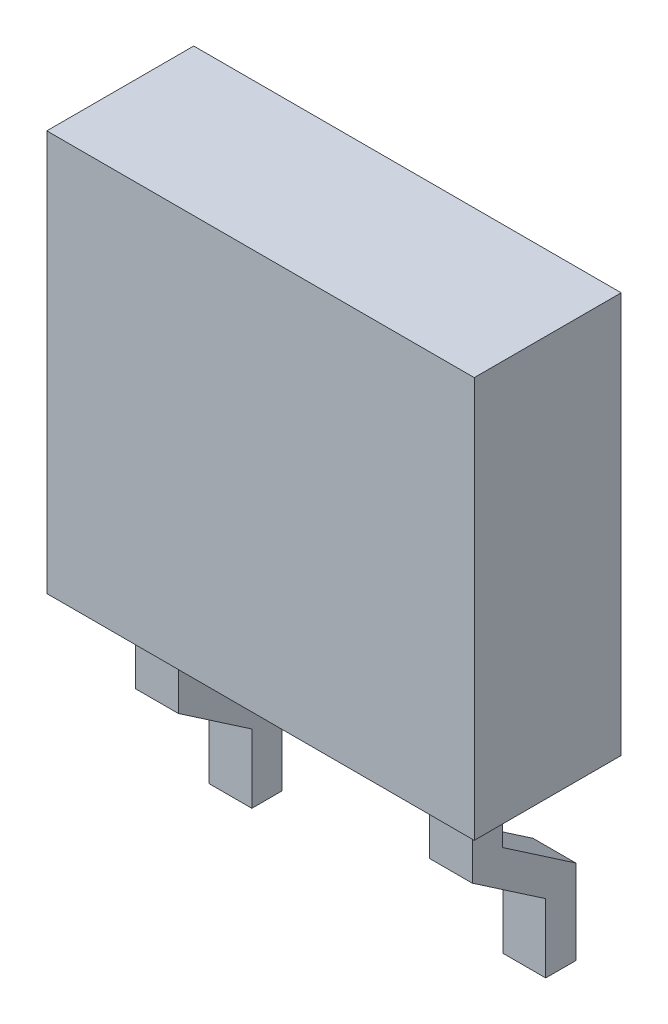
SolidWorks part; units mm, degrees
material "ABS"
ref_plane "Plan de face" through (0, 0, 0) normal (0, 0, 1) x (1, 0, 0)
ref_plane "Plan de dessus" through (0, 0, 0) normal (0, 1, 0) x (1, 0, 0)
ref_plane "Plan de droite" through (0, 0, 0) normal (1, 0, 0) x (0, 0, -1)
sketch "Esquisse1" plane through (0, 0, 0) normal (0, 0, 1) x (1, 0, 0)
  line L0 (3.2, 0) -> (3.2, -5.4078) construction
  line L1 (0, 0) -> (0.68, 0)
  line L2 (0, 0) -> (0, 6)
  line L3 (0, 6) -> (6.4, 6)
  line L4 (6.4, 0) -> (6.4, 6)
  line L5 (5.4, 1.3238) -> (5.4, -3.2603) construction
  line L6 (1.32, -3) -> (0.68, -3)
  line L7 (5.72, 0) -> (6.4, 0)
  line L8 (5.08, 0) -> (5.08, -3)
  line L9 (5.08, -3) -> (5.72, -3)
  line L10 (5.72, 0) -> (5.72, -3)
  line L11 (1.32, 0) -> (1.32, -3)
  line L12 (0.68, 0) -> (0.68, -3)
  line L13 (5.08, 0) -> (1.32, 0)
  dimension "D1" = 6.4
  dimension "D2" = 6
  dimension "D3" = 2.2
  dimension "D4" = 0.32
  dimension "D5" = 0.32
  dimension "D6" = 3
extrude "Extrusion1" add sketch "Esquisse1" along normal blind 2.2
sketch "Esquisse2" plane through (0.68, 0, 0) normal (-1, 0, 0) x (0, 0, 1)
  line L0 (0.45, -1.9712) -> (0.45, -3.3272)
  line L1 (1.55, 0) -> (4.1136, 0)
  line L2 (0, -1.7335) -> (0, -3.3272)
  line L3 (0.45, -3.3272) -> (4.1136, -3.3272)
  line L4 (4.1136, 0) -> (4.1136, -3.3272)
  line L6 (1.1, 0) -> (-1.2337, 0)
  line L7 (1.1, 0) -> (1.1, -0.9827)
  line L8 (0, -3.3272) -> (-1.2337, -3.3272)
  line L9 (-1.2337, 0) -> (-1.2337, -3.3272)
  line L10 (1.55, -1.2204) -> (0.45, -1.9712)
  line L12 (1.1, -0.9827) -> (0, -1.7335)
  line L16 (1.55, 0) -> (1.55, -1.2204)
extrude "Enlèv. mat.-Extru.1" cut sketch "Esquisse2" against normal through all
